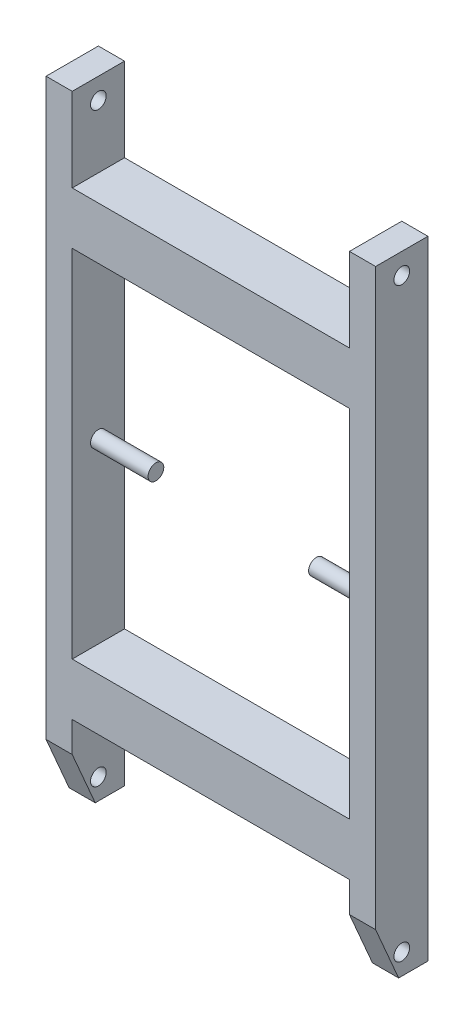
SolidWorks part; units mm, degrees
ref_plane "Front Plane" through (0, 0, 0) normal (0, 0, 1) x (1, 0, 0)
ref_plane "Top Plane" through (0, 0, 0) normal (0, 1, 0) x (1, 0, 0)
ref_plane "Right Plane" through (0, 0, 0) normal (1, 0, 0) x (0, 0, -1)
sketch "Sketch1" plane through (0, 0, 0) normal (0, 0, 1) x (1, 0, 0)
  line L0 (-7.2877, 248.8485) -> (17.7123, 248.8485)
  line L1 (-297.2877, 248.8485) -> (-272.2877, 248.8485)
  line L2 (-297.2877, 248.8485) -> (-297.2877, -351.1515)
  line L3 (-297.2877, -351.1515) -> (-272.2877, -351.1515)
  line L4 (-272.2877, 248.8485) -> (-272.2877, 168.8485)
  line L5 (-7.2877, 248.8485) -> (-7.2877, 168.8485)
  line L6 (17.7123, 248.8485) -> (17.7123, -351.1515)
  line L7 (-7.2877, -351.1515) -> (17.7123, -351.1515)
  line L8 (-272.2877, 118.8485) -> (-7.2877, 118.8485)
  line L9 (-272.2877, -221.1515) -> (-7.2877, -221.1515)
  line L10 (-7.2877, -271.1515) -> (-7.2877, -351.1515)
  line L11 (-272.2877, -271.1515) -> (-7.2877, -271.1515)
  line L12 (-7.2877, 118.8485) -> (-7.2877, -221.1515)
  line L13 (-272.2877, 168.8485) -> (-7.2877, 168.8485)
  line L14 (-272.2877, -271.1515) -> (-272.2877, -351.1515)
  line L15 (-272.2877, 118.8485) -> (-272.2877, -221.1515)
  dimension "D1" = 600
  dimension "D3" = 25
  dimension "D4" = 50
  dimension "D5" = 80
  dimension "D6" = 2
  dimension "D7" = 80
  dimension "D8" = 315
  dimension "D2" = 2
extrude "Boss-Extrude1" add sketch "Sketch1" along normal blind 50
sketch "Sketch2" plane through (17.7123, 0, 0) normal (1, 0, 0) x (0, 0, -1)
  line L0 (-50, 248.8485) -> (0, 248.8485) construction
  circle A0 centre (-26.5585, -51.1515) radius 7.5
  point P4 (-25, 248.8485)
  dimension "D1" = 15
  dimension "D2" = 300
extrude "Boss-Extrude2" add sketch "Sketch2" against normal blind 80
ref_plane "Plane2" through (-297.2877, 0, 0) normal (-1, 0, 0) x (0, 0, 1)
sketch "Sketch7" plane through (-297.2877, 0, 0) normal (-1, 0, 0) x (0, 0, 1)
  line L0 (50, 248.8485) -> (50, -351.1515) construction
  line L1 (50, -351.1515) -> (0, -351.1515) construction
  circle A0 centre (25, -51.1515) radius 7.5
  dimension "D1" = 25
  dimension "D2" = 300
extrude "Boss-Extrude3" add sketch "Sketch7" against normal blind 80
sketch "Sketch8" plane through (-297.2877, 0, 0) normal (-1, 0, 0) x (0, 0, 1)
  line L0 (50, 248.8485) -> (50, -351.1515) construction
  line L2 (50, -351.1515) -> (0, -351.1515) construction
  circle A0 centre (25, -331.1515) radius 7.5
  point P7 (25, -351.1515)
  dimension "D1" = 15
  dimension "D2" = 25
  dimension "D3" = 20
extrude "Cut-Extrude1" cut sketch "Sketch8" against normal blind 410
sketch "Sketch9" plane through (-297.2877, 0, 0) normal (-1, 0, 0) x (0, 0, 1)
  line L0 (50, 248.8485) -> (0, 248.8485) construction
  line L1 (50, 248.8485) -> (50, -351.1515) construction
  circle A0 centre (25, 228.8485) radius 7.5
  dimension "D1" = 20
  dimension "D2" = 25
extrude "Cut-Extrude2" cut sketch "Sketch9" against normal blind 410
sketch "Sketch11" plane through (0, 0, 0) normal (1, 0, 0) x (0, 0, -1)
  line L0 (-50, -351.1515) -> (-28, -351.1515)
  line L1 (-50, -351.1515) -> (0, -351.1515) construction
  line L2 (-28, -351.1515) -> (-50, -300.1515)
  line L3 (-50, -300.1515) -> (-50, -351.1515)
  dimension "D1" = 51
  dimension "D2" = 22
extrude "Cut-Extrude4" cut sketch "Sketch11" against normal through all both and the other way through all
